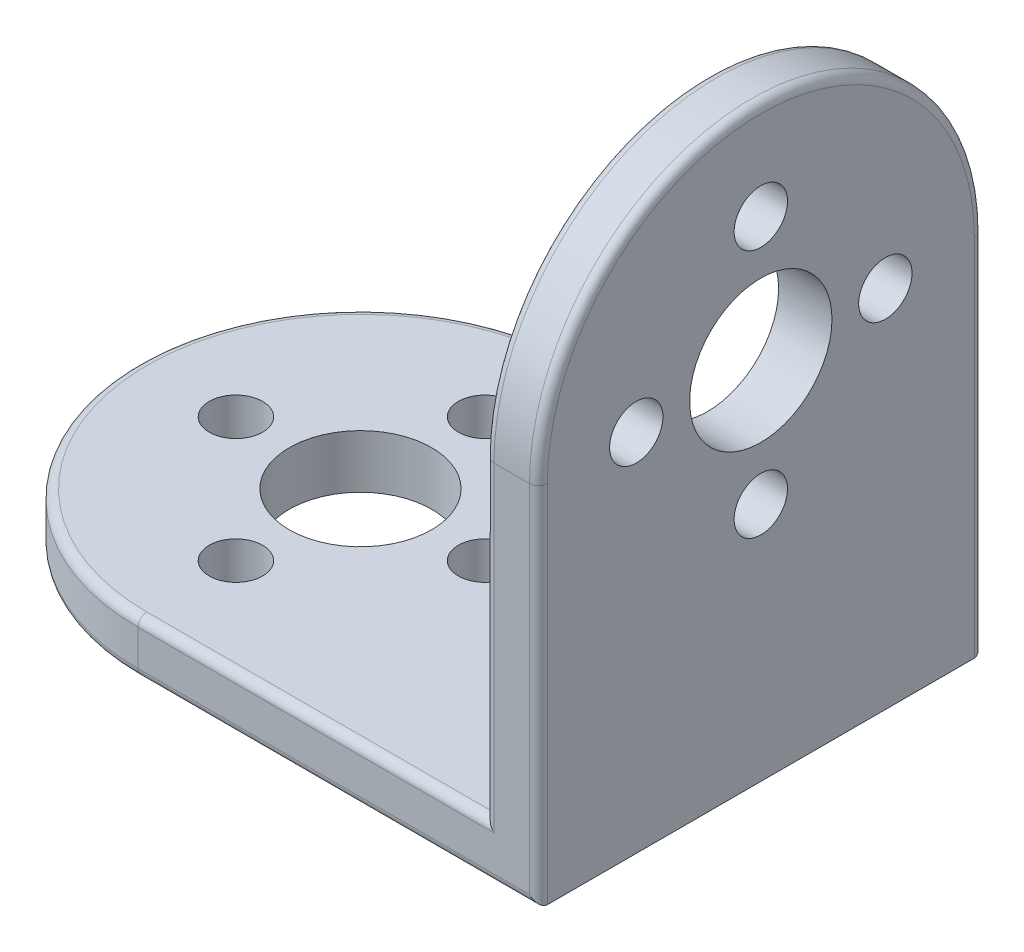
SolidWorks part; units mm, degrees
ref_plane "Front Plane" through (0, 0, 0) normal (0, 0, 1) x (1, 0, 0)
ref_plane "Top Plane" through (0, 0, 0) normal (0, 1, 0) x (1, 0, 0)
ref_plane "Right Plane" through (0, 0, 0) normal (1, 0, 0) x (0, 0, -1)
sketch "Sketch1" plane through (0, 0, 0) normal (0, 1, 0) x (1, 0, 0)
  line L1 (-5, 12.5) -> (17.5, 12.5)
  line L3 (-5, -12.5) -> (17.5, -12.5)
  line L4 (17.5, 12.5) -> (17.5, -12.5)
  line L5 (-13.2038, 9.4313) -> (17.5, -12.5) construction
  line L6 (-13.2038, -9.4313) -> (17.5, 12.5) construction
  arc A0 (-5, 12.5) -> (-5, -12.5) centre (-5, 0) ccw
  point P0 (0, 0)
  dimension "D2" = 25
extrude "Boss-Extrude1" add sketch "Sketch1" along normal blind 3 contours L1 L4 L3 A0
sketch "Sketch2" plane through (0, 3, 0) normal (0, 1, 0) x (1, 0, 0)
  line L0 (-5, -12.5) -> (17.5, -12.5) construction
  line L1 (17.5, 12.5) -> (14.5, 12.5)
  line L2 (17.5, 12.5) -> (17.5, -12.5)
  line L3 (17.5, -12.5) -> (14.5, -12.5)
  line L4 (14.5, 12.5) -> (14.5, -12.5)
  dimension "D1" = 3
extrude "Boss-Extrude2" add sketch "Sketch2" along normal blind 30
sketch "Sketch3" plane through (17.5, 0, 0) normal (1, 0, 0) x (0, 0, -1)
  line L1 (-12.5, 33) -> (12.5, 33)
  line L2 (-12.5, 33) -> (-12.5, 20.5)
  line L4 (12.5, 33) -> (12.5, 20.5)
  arc A0 (12.5, 20.5) -> (-12.5, 20.5) centre (0, 20.5) ccw
extrude "Cut-Extrude2" cut sketch "Sketch3" against normal blind 3
hole_wizard "Ø8.0mm Dowel Hole1" positions "Sketch4" profile "Sketch5" hole size "Ø8.0" standard "ISO" end condition through all
sketch "Sketch4" plane through (17.5, 0, 0) normal (1, 0, 0) x (0, 0, -1)
  point P0 (0, 20.5)
sketch "Sketch5" plane through (17.5, 20.5, 0) normal (0, 1, 0) x (0, 0, -1)
  line L0 (0, 0) -> (0, 35)
  line L1 (0, 35) -> (4, 35)
  line L2 (4, 35) -> (4, 0)
  line L5 (4, 0) -> (0, 0)
  line L11 (0, -6.35) -> (0, 107.95) construction
  dimension "Thru Hole Dia." = 8
  dimension "Thru Hole Depth" = 35
hole_wizard "Ø8.0mm Dowel Hole2" positions "Sketch6" profile "Sketch7" hole size "Ø8.0" standard "ISO" end condition through all
sketch "Sketch6" plane through (0, 3, 0) normal (0, 1, 0) x (1, 0, 0)
  point P0 (-5, 0)
sketch "Sketch7" plane through (-5, 3, 0) normal (1, 0, 0) x (0, 0, 1)
  line L0 (0, 0) -> (0, 3)
  line L1 (0, 3) -> (4, 3)
  line L2 (4, 3) -> (4, 0)
  line L5 (4, 0) -> (0, 0)
  line L11 (0, -6.35) -> (0, 107.95) construction
  dimension "Thru Hole Dia." = 8
  dimension "Thru Hole Depth" = 3
hole_wizard "Ø3.0mm Dowel Hole1" positions "Sketch8" profile "Sketch9" hole size "Ø3.0" standard "ISO" end condition through all
sketch "Sketch8" plane through (17.5, 0, 0) normal (1, 0, 0) x (0, 0, -1)
  circle A0 centre (0, 20.5) radius 4 construction
  point P0 (0, 27.5)
  point P10 (7, 20.5)
  point P11 (0, 13.5)
  point P12 (-7, 20.5)
  point P13 (0, 20.5)
  dimension "D1" = 7
  dimension "D2" = 4
sketch "Sketch9" plane through (17.5, 27.5, 0) normal (0, 1, 0) x (0, 0, -1)
  line L0 (0, 0) -> (0, 35)
  line L1 (0, 35) -> (1.5, 35)
  line L2 (1.5, 35) -> (1.5, 0)
  line L5 (1.5, 0) -> (0, 0)
  line L11 (0, -6.35) -> (0, 107.95) construction
  dimension "Thru Hole Dia." = 3
  dimension "Thru Hole Depth" = 35
hole_wizard "Ø3.0mm Dowel Hole2" positions "Sketch10" profile "Sketch11" hole size "Ø3.0" standard "ISO" end condition through all
sketch "Sketch10" plane through (0, 3, 0) normal (0, 1, 0) x (1, 0, 0)
  circle A0 centre (-5, 0) radius 4 construction
  point P0 (-12, 0)
  point P10 (-5, 7)
  point P11 (2, 0)
  point P12 (-5, -7)
  point P13 (-5, 0)
  dimension "D1" = 7
  dimension "D2" = 4
sketch "Sketch11" plane through (-12, 3, 0) normal (1, 0, 0) x (0, 0, 1)
  line L0 (0, 0) -> (0, 3)
  line L1 (0, 3) -> (1.5, 3)
  line L2 (1.5, 3) -> (1.5, 0)
  line L5 (1.5, 0) -> (0, 0)
  line L11 (0, -6.35) -> (0, 107.95) construction
  dimension "Thru Hole Dia." = 3
  dimension "Thru Hole Depth" = 3
fillet "Fillet1" radius 0.5 12 edges at (4.75, 3, -12.5) (6.25, 0, -12.5) (17.5, 10.25, -12.5) (14.5, 11.75, -12.5) (-17.5, 3, 0) (-17.5, 0, 0) (17.5, 10.25, 12.5) (6.25, 0, 12.5) (4.75, 3, 12.5) (14.5, 11.75, 12.5) (14.5, 33, 0) (17.5, 33, 0)
